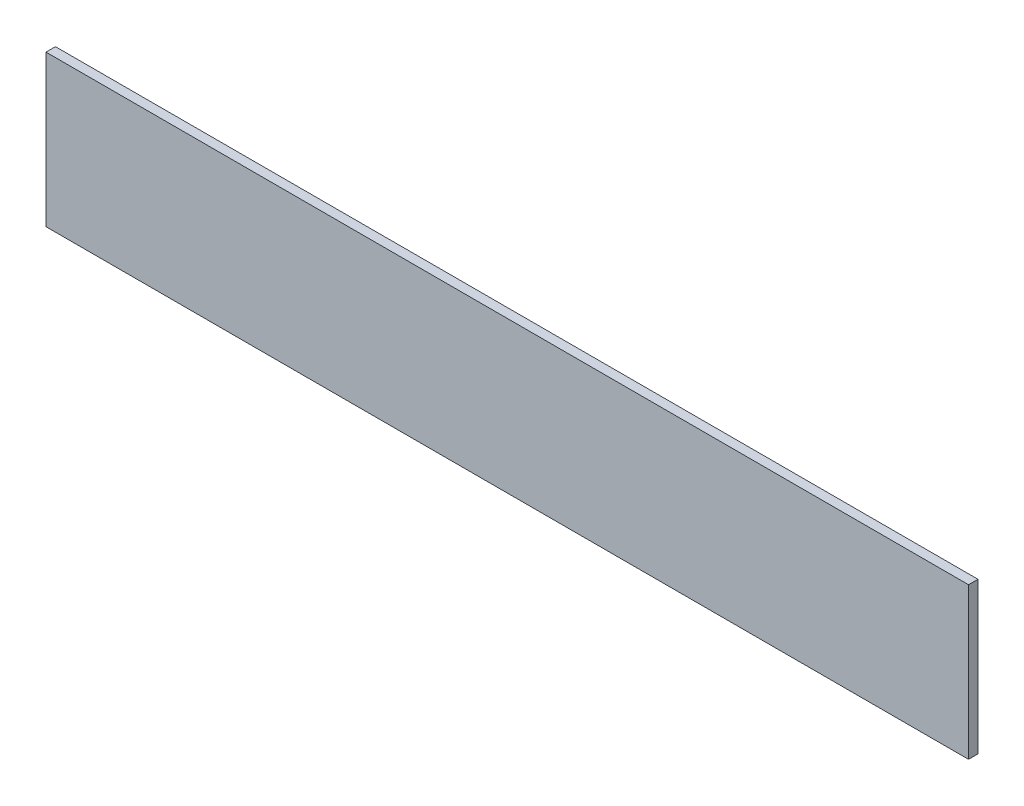
SolidWorks part; units mm, degrees
ref_plane "Front Plane" through (0, 0, 0) normal (0, 0, 1) x (1, 0, 0)
ref_plane "Top Plane" through (0, 0, 0) normal (0, 1, 0) x (1, 0, 0)
ref_plane "Right Plane" through (0, 0, 0) normal (1, 0, 0) x (0, 0, -1)
sketch "Sketch1" plane through (0, 0, 0) normal (0, 0, 1) x (1, 0, 0)
  line L0 (0, 0) -> (0, 101.6) construction
  line L1 (0, 0) -> (619.76, 0)
  line L2 (0, 0) -> (0, 101.6)
  line L3 (0, 101.6) -> (619.76, 101.6)
  line L4 (619.76, 0) -> (619.76, 101.6)
  line L5 (619.76, 0) -> (619.76, 101.6) construction
  dimension "D1" = 101.6
extrude "Boss-Extrude1" add sketch "Sketch1" along normal blind 6.35
